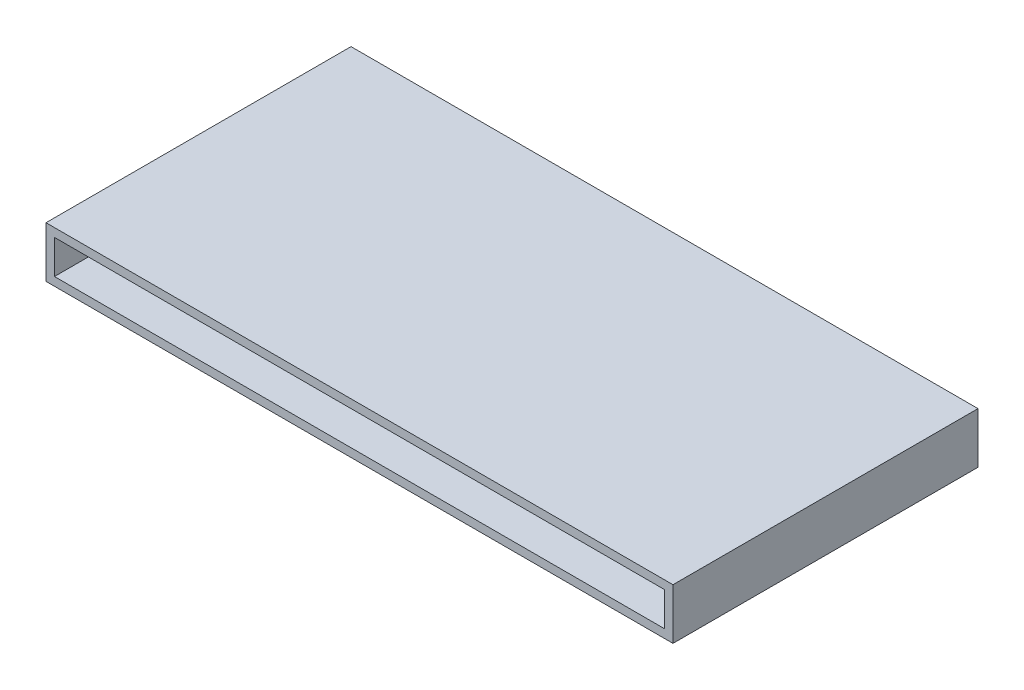
SolidWorks part; units mm, degrees
ref_plane "Front Plane" through (0, 0, 0) normal (0, 0, 1) x (1, 0, 0)
ref_plane "Top Plane" through (0, 0, 0) normal (0, 1, 0) x (1, 0, 0)
ref_plane "Right Plane" through (0, 0, 0) normal (1, 0, 0) x (0, 0, -1)
sketch "Sketch1" plane through (0, 0, 0) normal (0, 0, 1) x (1, 0, 0)
  line L1 (0, 0) -> (148, 0)
  line L2 (0, 0) -> (0, 12)
  line L3 (0, 12) -> (148, 12)
  line L4 (148, 0) -> (148, 12)
  line L6 (2, 2) -> (146, 2)
  line L7 (2, 2) -> (2, 10)
  line L8 (2, 10) -> (146, 10)
  line L9 (146, 2) -> (146, 10)
  dimension "D1" = 2
  dimension "D2" = 146
  dimension "D3" = 148
  dimension "D4" = 2
  dimension "D5" = 10
  dimension "D6" = 12
extrude "Profile" add sketch "Sketch1" along normal blind 72
sketch "Sketch2" plane through (0, 0, 0) normal (0, 0, 1) x (1, 0, 0)
  line L1 (2, 2) -> (146, 2)
  line L2 (2, 2) -> (2, 10)
  line L3 (2, 10) -> (146, 10)
  line L4 (146, 2) -> (146, 10)
  dimension "D1" = 144
  dimension "D2" = 8
extrude "Back" add sketch "Sketch2" along normal blind 2
equation "\"Profile_Depth\"= 72mm"
equation "\"D1@Profile\" = \"Profile_Depth\""
equation "\"Profile_Sketch_1\"= 2mm"
equation "\"D1@Sketch1\" = \"Profile_Sketch_1\""
equation "\"Profile_Sketch_2\"= 146mm"
equation "\"D2@Sketch1\" = \"Profile_Sketch_2\""
equation "\"Profile_Sketch_3\"= 148mm"
equation "\"D3@Sketch1\" = \"Profile_Sketch_3\""
equation "\"Profile_Sketch_4\"= 2mm"
equation "\"D4@Sketch1\" = \"Profile_Sketch_4\""
equation "\"Profile_Sketch_5\"= 10mm"
equation "\"D5@Sketch1\" = \"Profile_Sketch_5\""
equation "\"Profile_Sketch_6\"= 12mm"
equation "\"D6@Sketch1\" = \"Profile_Sketch_6\""
equation "\"Back_Depth\"= 2mm"
equation "\"D1@Back\" = \"Back_Depth\""
equation "\"Back_Sketch_1\"= 144mm"
equation "\"D1@Sketch2\" = \"Back_Sketch_1\""
equation "\"Back_Sketch_2\"= 8mm"
equation "\"D2@Sketch2\" = \"Back_Sketch_2\""
equation "\"EnvelopeWidth\"= 148mm"
equation "\"EnvelopeHeight\"= 12mm"
